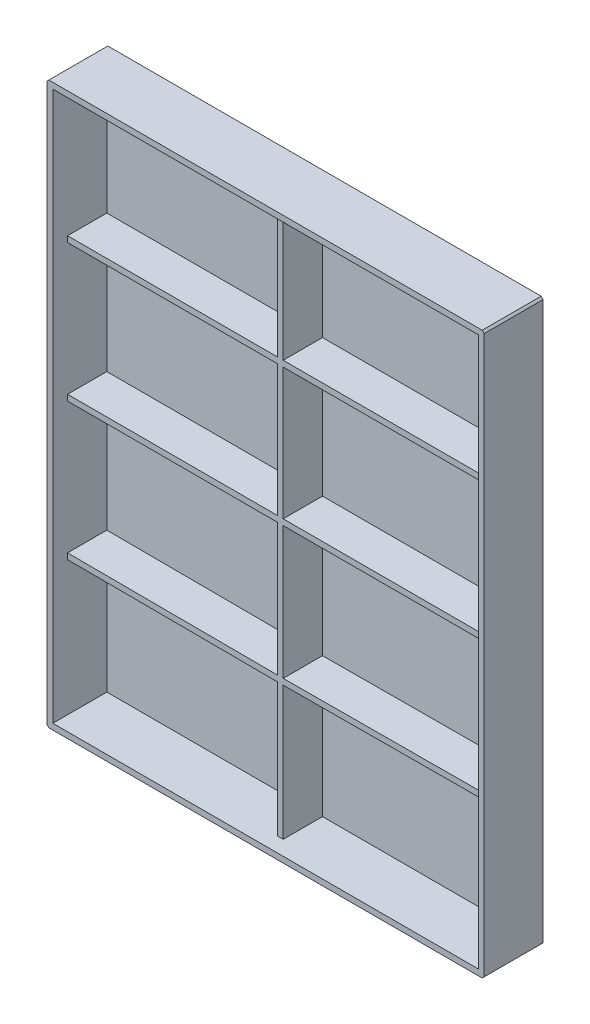
SolidWorks part; units mm, degrees
ref_plane "Front Plane" through (0, 0, 0) normal (1, 0, 0) x (0, 1, 0)
ref_plane "Top Plane" through (0, 0, 0) normal (0, 0, 1) x (0, 1, 0)
ref_plane "Right Plane" through (0, 0, 0) normal (0, 1, 0) x (-1, 0, 0)
sketch "Sketch1" plane through (0, 0, 0) normal (0, 0, 1) x (0, 1, 0)
  line L0 (-139.8, 108.3) -> (139.8, 108.3)
  line L1 (-139.5, -108) -> (139.5, -108) construction
  line L2 (-139.5, -108) -> (-139.5, 108) construction
  line L3 (-139.5, 108) -> (139.5, 108) construction
  line L4 (139.5, -108) -> (139.5, 108) construction
  line L5 (-139.5, -108) -> (139.5, 108) construction
  line L6 (-139.5, 108) -> (139.5, -108) construction
  line L7 (139.8, -108.3) -> (139.8, 108.3)
  line L8 (-139.8, -108.3) -> (139.8, -108.3)
  line L9 (-139.8, -108.3) -> (-139.8, 108.3)
  point P0 (0, 0)
  dimension "D1" = 279
  dimension "D2" = 216
  dimension "D3" = 0.3
extrude "Boss-Extrude1" add sketch "Sketch1" along normal blind 2.5
sketch "Sketch2" plane through (0, 0, 0) normal (0, 0, -1) x (1, 0, 0)
  line L0 (-111.3, 142.8) -> (-111.3, -142.8)
  line L1 (-111.3, -142.8) -> (111.3, -142.8)
  line L2 (111.3, -142.8) -> (111.3, 142.8)
  line L3 (111.3, 142.8) -> (-111.3, 142.8)
  line L4 (108.3, 139.8) -> (-108.3, 139.8)
  line L5 (-108.3, 139.8) -> (-108.3, -139.8)
  line L6 (-108.3, -139.8) -> (108.3, -139.8)
  line L7 (108.3, -139.8) -> (108.3, 139.8)
  line L8 (108.3, 139.8) -> (-108.3, 139.8)
  line L9 (-108.3, 139.8) -> (-108.3, -139.8)
  line L10 (-108.3, -139.8) -> (108.3, -139.8)
  line L11 (108.3, -139.8) -> (108.3, 139.8)
  dimension "D1" = 0
  dimension "D2" = 3
extrude "Boss-Extrude2 wall 30mm" add sketch "Sketch2" against normal blind 30
sketch "Sketch3" plane through (0, 0, 2.5) normal (0, 0, 1) x (1, 0, 0)
  line L0 (0, 139.8) -> (0, 0) construction
  line L1 (108.3, 139.8) -> (-108.3, 139.8) construction
  line L2 (1.5, 71.4) -> (108.3, 71.4)
  line L3 (0, 0) -> (-108.3, 0) construction
  line L4 (-1.5, 71.4) -> (-108.3, 71.4)
  line L5 (-108.3, -139.8) -> (-108.3, 139.8) construction
  line L6 (0, 69.9) -> (108.3, 69.9) construction
  line L7 (108.3, 139.8) -> (108.3, -139.8) construction
  line L8 (1.5, -1.5) -> (108.3, -1.5)
  line L9 (-1.5, 1.5) -> (-108.3, 1.5)
  line L10 (0, 69.9) -> (-108.3, 69.9) construction
  line L11 (-108.3, 139.8) -> (-108.3, -139.8) construction
  line L12 (0, 0) -> (108.3, 0) construction
  line L13 (108.3, -139.8) -> (108.3, 139.8) construction
  line L14 (-1.5, 139.8) -> (-1.5, 71.4)
  line L15 (0, 0) -> (0, -139.8) construction
  line L16 (-108.3, -139.8) -> (108.3, -139.8) construction
  line L17 (1.5, 68.4) -> (108.3, 68.4)
  line L18 (-1.5, 68.4) -> (-108.3, 68.4)
  line L19 (1.5, 1.5) -> (108.3, 1.5)
  line L20 (-1.5, -1.5) -> (-108.3, -1.5)
  line L21 (1.5, 139.8) -> (1.5, 71.4)
  line L22 (-1.5, -1.5) -> (-1.5, -68.85)
  line L23 (1.5, -1.5) -> (1.5, -68.85)
  line L24 (1.5, -71.85) -> (108.3, -71.4)
  line L25 (1.5, -68.85) -> (108.3, -68.4)
  line L26 (-1.5, -68.85) -> (-108.3, -68.4)
  line L27 (-1.5, -71.85) -> (-108.3, -71.4)
  line L28 (1.5, 139.8) -> (-1.5, 139.8)
  line L29 (-108.3, 71.4) -> (-108.3, 68.4)
  line L30 (108.3, 71.4) -> (108.3, 68.4)
  line L31 (108.3, -1.5) -> (108.3, 1.5)
  line L32 (-108.3, 1.5) -> (-108.3, -1.5)
  line L33 (-108.3, -71.4) -> (-108.3, -68.4)
  line L34 (108.3, -71.4) -> (108.3, -68.4)
  line L35 (1.5, -139.8) -> (-1.5, -139.8)
  line L36 (1.5, 68.4) -> (1.5, 1.5)
  line L37 (1.5, 139.8) -> (1.5, 0) construction
  line L38 (0, 71.4) -> (108.3, 71.4) construction
  line L39 (-1.5, 68.4) -> (-1.5, 1.5)
  line L40 (-1.5, 139.8) -> (-1.5, 0) construction
  line L41 (0, 71.4) -> (-108.3, 71.4) construction
  line L42 (0, 68.4) -> (-108.3, 68.4) construction
  line L43 (0, 68.4) -> (108.3, 68.4) construction
  line L44 (0, 1.5) -> (-108.3, 1.5) construction
  line L45 (0, 1.5) -> (108.3, 1.5) construction
  line L46 (1.5, 0) -> (1.5, -139.8) construction
  line L47 (0, -1.5) -> (108.3, -1.5) construction
  line L48 (0, -1.5) -> (-108.3, -1.5) construction
  line L49 (-1.5, 0) -> (-1.5, -139.8) construction
  line L50 (-1.5, -71.85) -> (-1.5, -139.8)
  line L51 (1.5, -71.85) -> (1.5, -139.8)
  dimension "D1" = 1.5
  dimension "D2" = 1.5
  dimension "D3" = 1.5
  dimension "D4" = 1.5
extrude "Boss-Extrude3" add sketch "Sketch3" along normal blind 20
chamfer "Chamfer1" distance 1 angle 45 4 edges at (-111.3, -142.8, 15) (111.3, -142.8, 15) (-111.3, 142.8, 15) (111.3, 142.8, 15)
